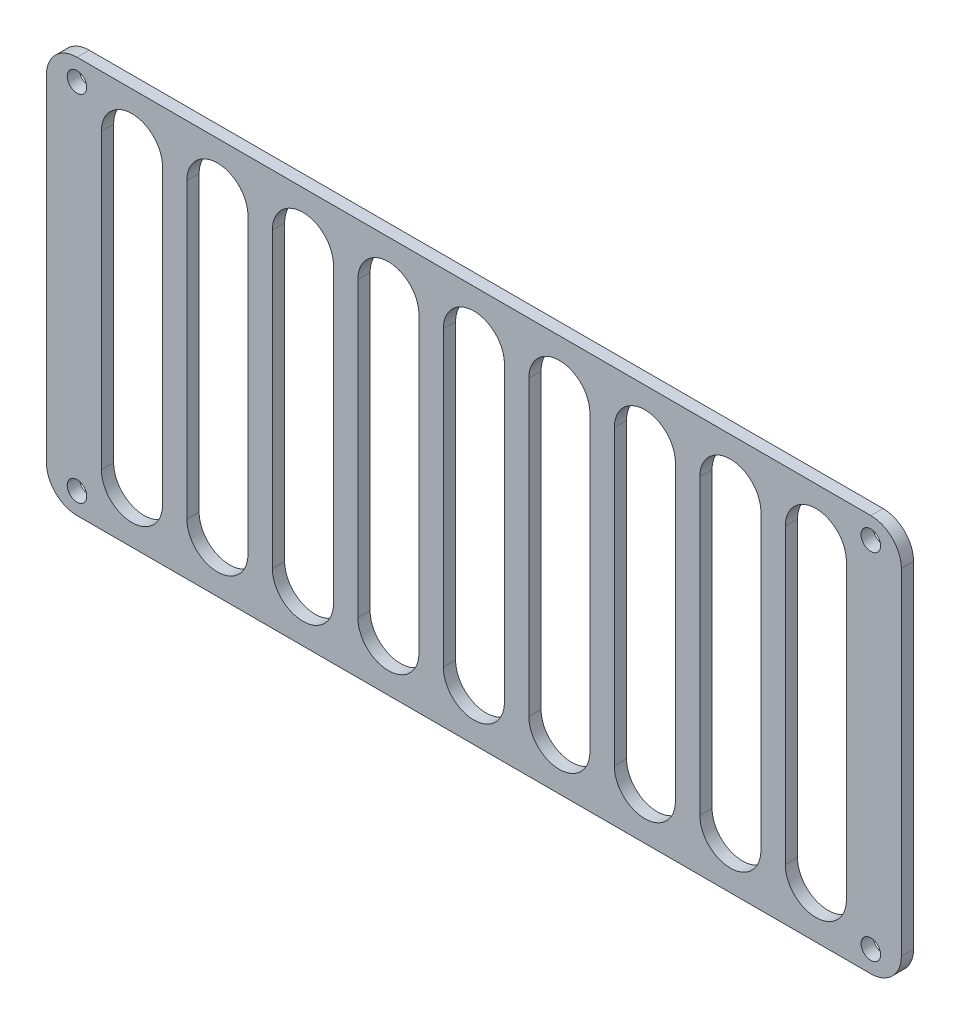
SolidWorks part; units mm, degrees
material "A-玻璃纤维"
ref_plane "前视基准面" through (0, 0, 0) normal (0, 0, 1) x (1, 0, 0)
ref_plane "上视基准面" through (0, 0, 0) normal (0, 1, 0) x (1, 0, 0)
ref_plane "右视基准面" through (0, 0, 0) normal (1, 0, 0) x (0, 0, -1)
sketch "草图1" plane through (0, 0, 0) normal (0, 0, 1) x (1, 0, 0)
  line L1 (70, 32.5) -> (-70, 32.5)
  line L2 (70, 32.5) -> (70, -32.5)
  line L3 (70, -32.5) -> (-70, -32.5)
  line L4 (-70, 32.5) -> (-70, -32.5)
  line L5 (0, -32.5) -> (0, 32.5) construction
  line L6 (70, 0) -> (-70, 0) construction
  point P0 (0, 0)
  dimension "D1" = 140
  dimension "D2" = 65
extrude "凸台-拉伸1" add sketch "草图1" along normal blind 2
sketch "草图2" plane through (0, 0, 2) normal (0, 0, 1) x (1, 0, 0)
  line L0 (0, 47.5982) -> (0, -42.384) construction
  line L1 (-86.4067, 0) -> (105.1778, 0) construction
  circle A0 centre (-65, 29) radius 1.6
  circle A1 centre (65, 29) radius 1.6
  circle A2 centre (65, -29) radius 1.6
  circle A3 centre (-65, -29) radius 1.6
  dimension "D3" = 3.2
  dimension "D1" = 65
  dimension "D2" = 29
extrude "切除-拉伸1" cut sketch "草图2" against normal blind 2
sketch "草图3" plane through (0, 0, 2) normal (0, 0, 1) x (1, 0, 0)
  line L0 (-56, 24) -> (-56, -24) construction
  line L1 (-51, 24) -> (-51, -24)
  line L2 (-61, 24) -> (-61, -24)
  line L3 (-42, 24) -> (-42, -24) construction
  line L4 (-37, 24) -> (-37, -24)
  line L5 (-47, 24) -> (-47, -24)
  line L6 (-28, 24) -> (-28, -24) construction
  line L7 (-23, 24) -> (-23, -24)
  line L8 (-33, 24) -> (-33, -24)
  line L9 (-14, 24) -> (-14, -24) construction
  line L10 (-9, 24) -> (-9, -24)
  line L11 (-19, 24) -> (-19, -24)
  line L12 (0, 24) -> (0, -24) construction
  line L13 (5, 24) -> (5, -24)
  line L14 (-5, 24) -> (-5, -24)
  line L15 (14, 24) -> (14, -24) construction
  line L16 (19, 24) -> (19, -24)
  line L17 (9, 24) -> (9, -24)
  line L18 (28, 24) -> (28, -24) construction
  line L19 (33, 24) -> (33, -24)
  line L20 (23, 24) -> (23, -24)
  line L21 (42, 24) -> (42, -24) construction
  line L22 (47, 24) -> (47, -24)
  line L23 (37, 24) -> (37, -24)
  line L24 (56, 24) -> (56, -24) construction
  line L25 (61, 24) -> (61, -24)
  line L26 (51, 24) -> (51, -24)
  arc A0 (-51, 24) -> (-61, 24) centre (-56, 24) ccw
  arc A1 (-61, -24) -> (-51, -24) centre (-56, -24) ccw
  circle A2 centre (-65, -29) radius 1.6 construction
  arc A3 (-37, 24) -> (-47, 24) centre (-42, 24) ccw
  arc A4 (-47, -24) -> (-37, -24) centre (-42, -24) ccw
  arc A5 (-23, 24) -> (-33, 24) centre (-28, 24) ccw
  arc A6 (-33, -24) -> (-23, -24) centre (-28, -24) ccw
  arc A7 (-9, 24) -> (-19, 24) centre (-14, 24) ccw
  arc A8 (-19, -24) -> (-9, -24) centre (-14, -24) ccw
  arc A9 (5, 24) -> (-5, 24) centre (0, 24) ccw
  arc A10 (-5, -24) -> (5, -24) centre (0, -24) ccw
  arc A11 (19, 24) -> (9, 24) centre (14, 24) ccw
  arc A12 (9, -24) -> (19, -24) centre (14, -24) ccw
  arc A13 (33, 24) -> (23, 24) centre (28, 24) ccw
  arc A14 (23, -24) -> (33, -24) centre (28, -24) ccw
  arc A15 (47, 24) -> (37, 24) centre (42, 24) ccw
  arc A16 (37, -24) -> (47, -24) centre (42, -24) ccw
  arc A17 (61, 24) -> (51, 24) centre (56, 24) ccw
  arc A18 (51, -24) -> (61, -24) centre (56, -24) ccw
  point P2 (-56, 0)
  point P14 (-42, 0)
  point P21 (-28, 0)
  point P28 (-14, 0)
  point P35 (0, 0)
  point P42 (14, 0)
  point P49 (28, 0)
  point P56 (42, 0)
  point P61 (56, 0)
  dimension "D1" = 10
  dimension "D2" = 9
  dimension "D3" = 48
  dimension "D5" = 14
  dimension "D4" = 9
extrude "切除-拉伸2" cut sketch "草图3" against normal blind 2
fillet "圆角1" radius 5 4 edges at (70, -32.5, 1) (70, 32.5, 1) (-70, 32.5, 1) (-70, -32.5, 1)
